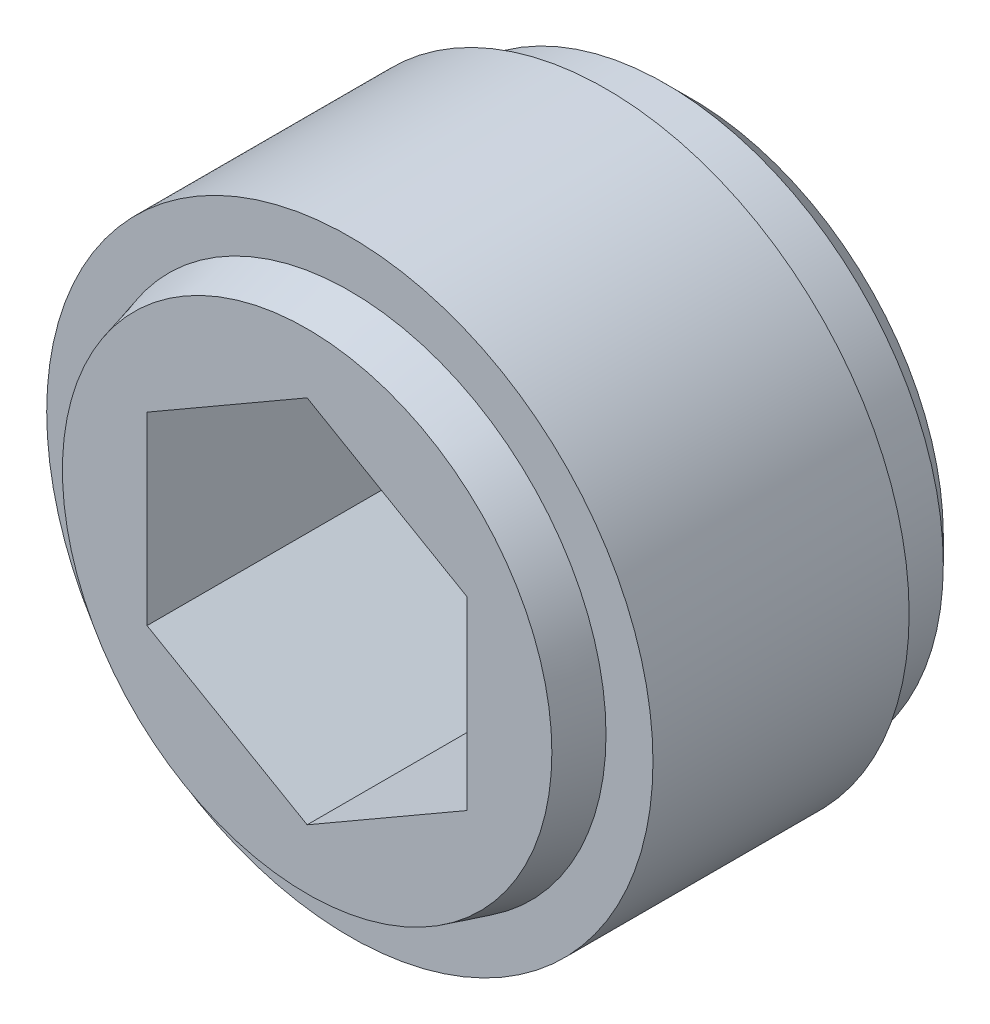
SolidWorks part; units mm, degrees
ref_plane "Front Plane" through (0, 0, 0) normal (0, 0, 1) x (1, 0, 0)
ref_plane "Top Plane" through (0, 0, 0) normal (0, 1, 0) x (1, 0, 0)
ref_plane "Right Plane" through (0, 0, 0) normal (1, 0, 0) x (0, 0, -1)
sketch "Sketch1" plane through (0, 0, 0) normal (0, 0, 1) x (1, 0, 0)
  circle A0 centre (0, 0) radius 4.5085
  dimension "D1" = 9.017
extrude "Boss-Extrude1" add sketch "Sketch1" along normal blind 5.08
cosmetic thread "Cosmetic Thread1" parameters "D2"=6.6777
sketch "Sketch2" plane through (0, 0, 5.08) normal (0, 0, 1) x (1, 0, 0)
  circle A0 centre (0, 0) radius 3.81
  dimension "D1" = 7.62
extrude "Boss-Extrude2" add sketch "Sketch2" along normal blind 0.635 draft 15
sketch "Sketch3" plane through (0, 0, 0) normal (0, 0, -1) x (-1, 0, 0)
  circle A0 centre (0, 0) radius 4.1275
  circle A1 centre (0, 0) radius 4.5085 construction
  circle A2 centre (0, 0) radius 4.5085
  dimension "D1" = 8.255
extrude "Cut-Extrude1" cut sketch "Sketch3" against normal blind 1.27
chamfer "Chamfer1" distance 0.381 1 edges at (-4.1275, 0, 0)
sketch "Sketch4" plane through (0, 0, 0) normal (0, 0, -1) x (-1, 0, 0)
  line L1 (0, 2.7496) -> (-2.3812, 1.3748)
  line L2 (-2.3812, 1.3748) -> (-2.3812, -1.3748)
  line L3 (-2.3812, -1.3748) -> (0, -2.7496)
  line L4 (0, -2.7496) -> (2.3812, -1.3748)
  line L5 (2.3812, -1.3748) -> (2.3812, 1.3748)
  line L6 (2.3812, 1.3748) -> (0, 2.7496)
  circle A0 centre (0, 0) radius 2.3813 construction
  dimension "D1" = 4.7625
extrude "Cut-Extrude2" cut sketch "Sketch4" against normal through all
